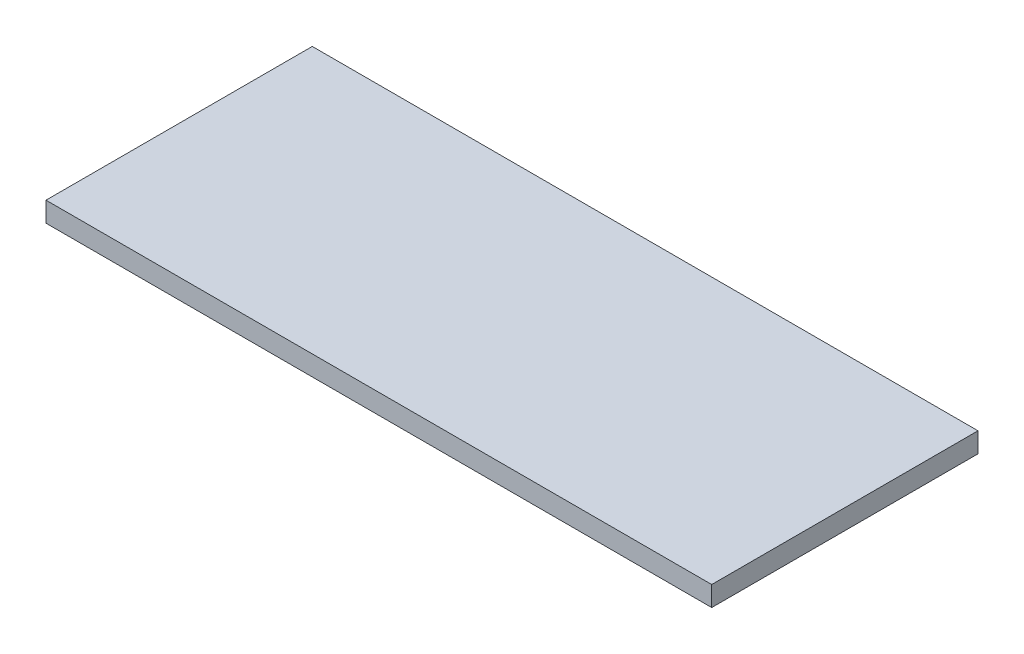
SolidWorks part; units mm, degrees
ref_plane "Спереди" through (0, 0, 0) normal (0, 0, 1) x (1, 0, 0)
ref_plane "Сверху" through (0, 0, 0) normal (0, 1, 0) x (1, 0, 0)
ref_plane "Справа" through (0, 0, 0) normal (1, 0, 0) x (0, 0, -1)
sketch "Эскиз1" plane through (0, 0, 0) normal (0, 1, 0) x (1, 0, 0)
  line L0 (-250, 100) -> (250, -100) construction
  line L1 (-250, 100) -> (250, 100)
  line L2 (-250, 100) -> (-250, -100)
  line L3 (-250, -100) -> (250, -100)
  line L4 (250, 100) -> (250, -100)
  point P4 (0, 0)
  dimension "D1" = 200
  dimension "D2" = 500
extrude "Бобышка-Вытянуть1" add sketch "Эскиз1" against normal blind 15
equation "\"L\"=500"
equation "\"B\"=200"
equation "\"D1@Эскиз1\" = \"B\""
equation "\"D2@Эскиз1\" = \"L\""
